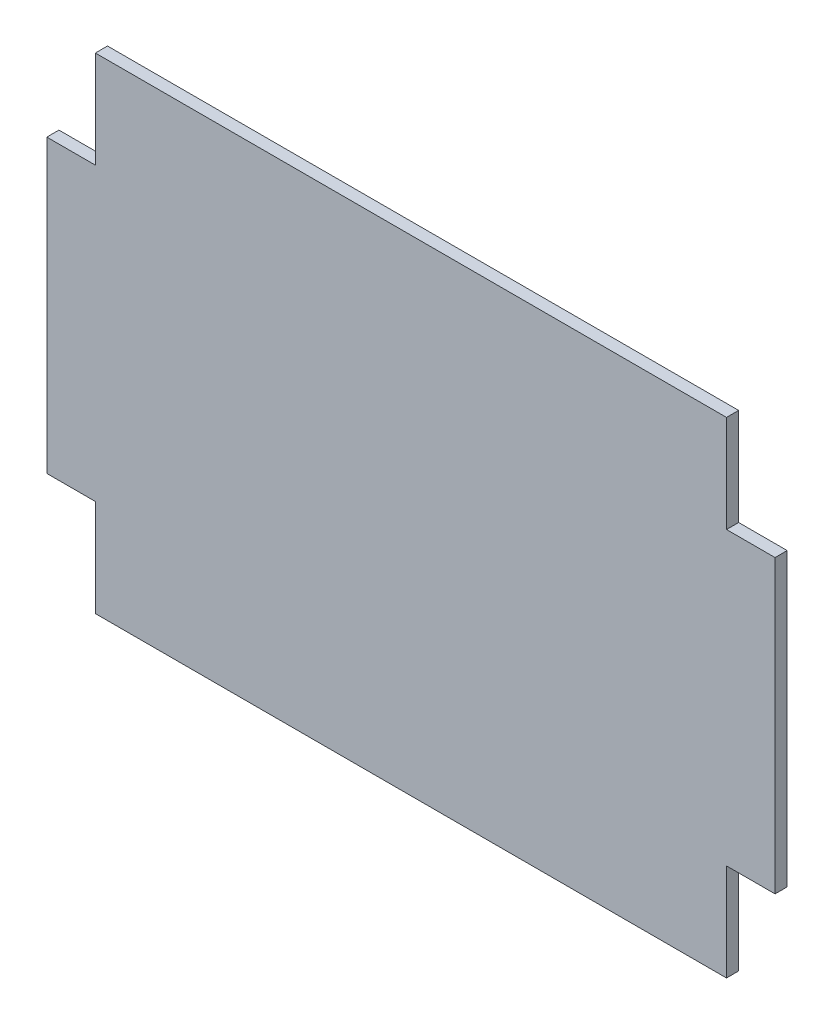
SolidWorks part; units mm, degrees
ref_plane "Front Plane" through (0, 0, 0) normal (0, 0, 1) x (1, 0, 0)
ref_plane "Top Plane" through (0, 0, 0) normal (0, 1, 0) x (1, 0, 0)
ref_plane "Right Plane" through (0, 0, 0) normal (1, 0, 0) x (0, 0, -1)
sketch "Sketch1" plane through (0, 0, 0) normal (0, 0, 1) x (1, 0, 0)
  line L1 (-150, 100) -> (150, 100)
  line L2 (-150, 100) -> (-150, -100)
  line L3 (-150, -100) -> (150, -100)
  line L4 (150, 100) -> (150, -100)
  line L5 (-150, 100) -> (150, -100) construction
  line L6 (-150, -100) -> (150, 100) construction
  point P0 (0, 0)
  dimension "D1" = 300
  dimension "D2" = 200
extrude "Boss-Extrude1" add sketch "Sketch1" along normal blind 5
sketch "Sketch3" plane through (0, 0, 5) normal (0, 0, 1) x (1, 0, 0)
  line L1 (-150, -100) -> (-130, -100)
  line L2 (-150, -100) -> (-150, -80)
  line L3 (-150, -80) -> (-130, -80)
  line L4 (-130, -100) -> (-130, -80)
  line L5 (-150, 100) -> (-130, 100)
  line L6 (-150, 100) -> (-150, 60)
  line L7 (-150, 60) -> (-130, 60)
  line L8 (-130, 100) -> (-130, 60)
  line L9 (150, 100) -> (130, 100)
  line L10 (150, 100) -> (150, 60)
  line L11 (150, 60) -> (130, 60)
  line L12 (130, 100) -> (130, 60)
  line L13 (150, -100) -> (130, -100)
  line L14 (150, -100) -> (150, -80)
  line L15 (150, -80) -> (130, -80)
  line L16 (130, -100) -> (130, -80)
  dimension "D1" = 20
  dimension "D2" = 20
  dimension "D3" = 40
extrude "Cut-Extrude1" cut sketch "Sketch3" against normal blind 5
sketch "Sketch4" plane through (0, 0, 0) normal (0, 0, -1) x (-1, 0, 0)
  line L0 (-150, -80) -> (-150, 60) construction
  line L1 (-130, -100) -> (-150, -100)
  line L2 (-130, -100) -> (-130, -60)
  line L3 (-130, -60) -> (-150, -60)
  line L4 (-150, -100) -> (-150, -60)
  line L5 (150, 60) -> (150, -80) construction
  line L6 (130, -100) -> (150, -100)
  line L7 (130, -100) -> (130, -60)
  line L8 (130, -60) -> (150, -60)
  line L9 (150, -100) -> (150, -60)
  dimension "D1" = 40
  dimension "D2" = 40
extrude "Cut-Extrude2" cut sketch "Sketch4" against normal blind 10
